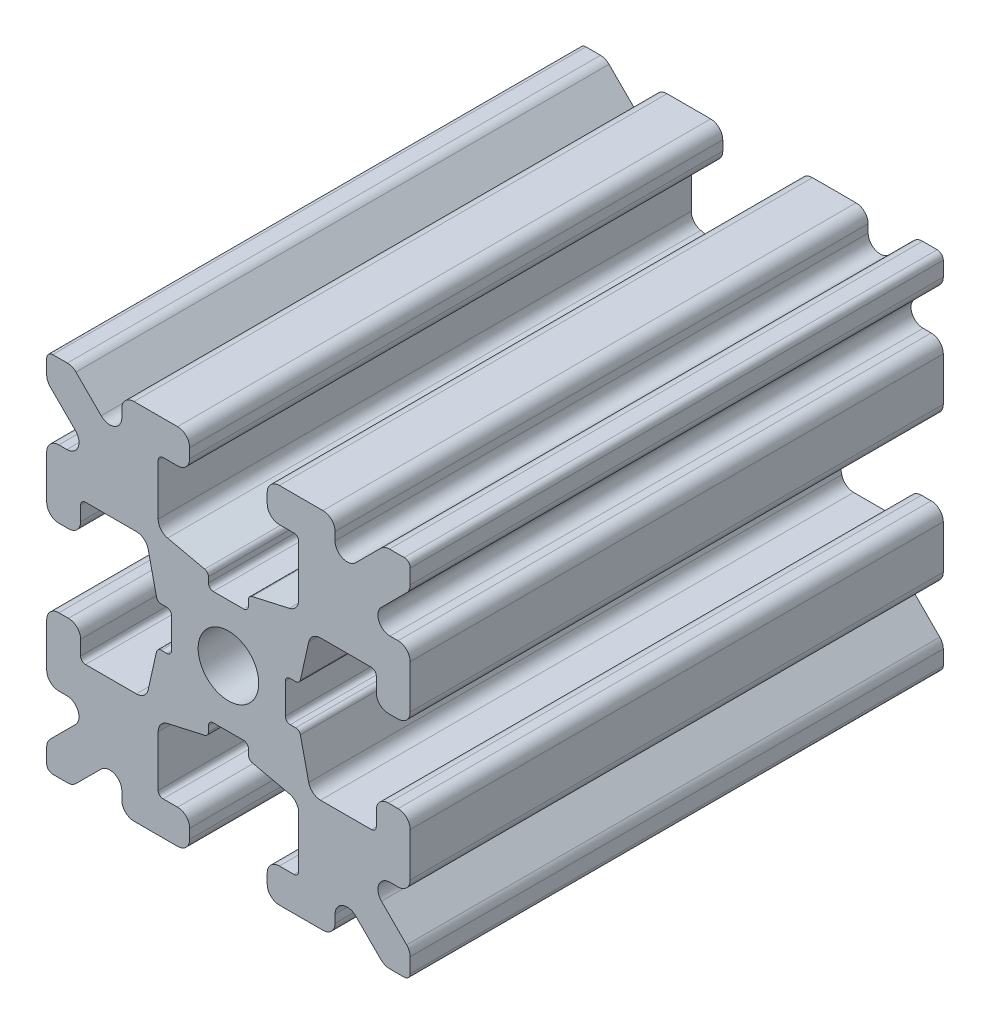
SolidWorks part; units mm, degrees
ref_plane "Front Plane" through (0, 0, 0) normal (0, 0, 1) x (1, 0, 0)
ref_plane "Top Plane" through (0, 0, 0) normal (0, 1, 0) x (1, 0, 0)
ref_plane "Right Plane" through (0, 0, 0) normal (1, 0, 0) x (0, 0, -1)
sketch "Sketch1" plane through (0, 0, 0) normal (0, 0, 1) x (1, 0, 0)
  line L1 (-7.5, -7.5) -> (7.5, -7.5)
  line L2 (-7.5, -7.5) -> (-7.5, 7.5)
  line L3 (-7.5, 7.5) -> (7.5, 7.5)
  line L4 (7.5, -7.5) -> (7.5, 7.5)
  line L5 (-7.5, -7.5) -> (7.5, 7.5) construction
  line L6 (-7.5, 7.5) -> (7.5, -7.5) construction
  circle A0 centre (0, 0) radius 1.25
  point P0 (0, 0)
  dimension "D2" = 2.5
  dimension "D1" = 15
extrude "Boss-Extrude1" add sketch "Sketch1" along normal mid plane 22
fillet "Fillet1" radius 0.25 4 edges at (7.5, -7.5, 0) (-7.5, -7.5, 0) (7.5, 7.5, 0) (-7.5, 7.5, 0)
sketch "Sketch2" plane through (0, 0, 11) normal (0, 0, 1) x (1, 0, 0)
  line L0 (-7.5, 7.25) -> (-7.5, -7.25) construction
  line L1 (-7.5, 1.6) -> (-6.1, 1.6)
  line L2 (-7.5, 1.6) -> (-7.5, -1.6)
  line L3 (-7.5, -1.6) -> (-6.1, -1.6)
  line L4 (-6.1, 1.6) -> (-6.1, 2.9)
  line L5 (0, 0) -> (-12.1036, 0) construction
  line L6 (-6.1, -2.9) -> (-3.4, -2.9)
  line L7 (0, 0) -> (-7.25, 7.25) construction
  line L8 (-6.1, 2.9) -> (-3.4, 2.9)
  line L9 (-3.4, -2.9) -> (-3.4, 2.9)
  line L10 (55, 0) -> (-55, 0) construction
  line L11 (-6.1, -2.9) -> (-6.1, -1.6)
  line L12 (2.9, 6.1) -> (1.6, 6.1)
  line L13 (2.9, 3.4) -> (-2.9, 3.4)
  line L14 (-2.9, 6.1) -> (-2.9, 3.4)
  line L15 (2.9, 6.1) -> (2.9, 3.4)
  line L16 (-1.6, 6.1) -> (-2.9, 6.1)
  line L17 (1.6, 7.5) -> (1.6, 6.1)
  line L18 (-1.6, 7.5) -> (1.6, 7.5)
  line L19 (-1.6, 7.5) -> (-1.6, 6.1)
  line L20 (-1.6, -7.5) -> (-1.6, -6.1)
  line L21 (-1.6, -7.5) -> (1.6, -7.5)
  line L22 (1.6, -7.5) -> (1.6, -6.1)
  line L23 (-1.6, -6.1) -> (-2.9, -6.1)
  line L24 (2.9, -6.1) -> (2.9, -3.4)
  line L25 (-2.9, -6.1) -> (-2.9, -3.4)
  line L26 (2.9, -3.4) -> (-2.9, -3.4)
  line L27 (2.9, -6.1) -> (1.6, -6.1)
  line L28 (6.1, -2.9) -> (6.1, -1.6)
  line L29 (3.4, -2.9) -> (3.4, 2.9)
  line L30 (6.1, 2.9) -> (3.4, 2.9)
  line L31 (6.1, -2.9) -> (3.4, -2.9)
  line L32 (6.1, 1.6) -> (6.1, 2.9)
  line L33 (7.5, -1.6) -> (6.1, -1.6)
  line L34 (7.5, 1.6) -> (7.5, -1.6)
  line L35 (7.5, 1.6) -> (6.1, 1.6)
  dimension "D1" = 3.2
  dimension "D2" = 5.8
  dimension "D3" = 1.4
  dimension "D4" = 2.7
extrude "Cut-Extrude1" cut sketch "Sketch2" against normal through all
sketch "Sketch4" plane through (0, 0, 11) normal (0, 0, 1) x (1, 0, 0)
  line L0 (-3.4, 2.9) -> (-2.75, 0)
  line L1 (55, 0) -> (-55, 0) construction
  line L2 (-2.75, 0) -> (-3.4, -2.9)
  line L3 (-3.4, -2.9) -> (-3.4, 2.9) construction
  line L4 (-3.4, 2.9) -> (-3.4, -2.9)
  line L5 (-2.9, 3.4) -> (0, 2.75)
  line L6 (0, 2.75) -> (2.9, 3.4)
  line L7 (2.9, 3.4) -> (-2.9, 3.4)
  line L8 (3.4, 2.9) -> (2.75, 0)
  line L9 (2.75, 0) -> (3.4, -2.9)
  line L10 (3.4, -2.9) -> (3.4, 2.9)
  line L11 (-2.9, -3.4) -> (0, -2.75)
  line L12 (0, -2.75) -> (2.9, -3.4)
  line L13 (2.9, -3.4) -> (-2.9, -3.4)
  circle A2 centre (0, 0) radius 2.75
  circle A3 centre (0, 0) radius 2.75 construction
  dimension "D1" = 1.5
extrude "Cut-Extrude3" cut sketch "Sketch4" against normal through all
fillet "Fillet3" radius 0.5 16 edges at (-6.1, -1.6, 0) (-7.5, -1.6, 0) (-6.1, 1.6, 0) (-7.5, 1.6, 0) (-1.6, -7.5, 0) (-1.6, -6.1, 0) (1.6, -7.5, 0) (1.6, -6.1, 0) (6.1, -1.6, 0) (7.5, -1.6, 0) (7.5, 1.6, 0) (6.1, 1.6, 0) (1.6, 7.5, 0) (1.6, 6.1, 0) (-1.6, 7.5, 0) (-1.6, 6.1, 0)
fillet "Fillet4" radius 0.5 8 edges at (-3.4, 2.9, 0) (-3.4, -2.9, 0) (2.9, -3.4, 0) (-2.9, -3.4, 0) (3.4, -2.9, 0) (3.4, 2.9, 0) (-2.9, 3.4, 0) (2.9, 3.4, 0)
fillet "Fillet5" radius 3 4 edges at (0, -2.75, 0) (2.75, 0, 0) (-2.75, 0, 0) (0, 2.75, 0)
fillet "Fillet6" radius 0.2 8 edges at (-2.9, -6.1, 0) (2.9, -6.1, 0) (6.1, -2.9, 0) (6.1, 2.9, 0) (2.9, 6.1, 0) (-2.9, 6.1, 0) (-6.1, -2.9, 0) (-6.1, 2.9, 0)
sketch "Sketch5" plane through (0, 0, 11) normal (0, 0, 1) x (1, 0, 0)
  line L0 (0, 0) -> (-7.25, 7.25) construction
  line L1 (-7.5, 6.4393) -> (-5.4607, 4.4)
  line L2 (-6.4393, 7.5) -> (-4.4, 5.4607)
  line L3 (-7.5, 4.4) -> (-5.4607, 4.4)
  line L4 (-3.8003, 2.9) -> (-5.9, 2.9) construction
  line L5 (0, 0) -> (-12.1819, 0) construction
  line L6 (-4.4, 7.5) -> (-4.4, 5.4607)
  line L7 (-2.9, 5.9) -> (-2.9, 3.8003) construction
  line L8 (-7.5, 6.4393) -> (-7.5, 4.4)
  line L9 (-7.5, 7.25) -> (-7.5, 2.1) construction
  line L10 (2.1, -7.5) -> (7.25, -7.5) construction
  line L11 (7.5, -7.25) -> (7.5, -2.1) construction
  line L12 (7.25, 7.5) -> (2.1, 7.5) construction
  line L13 (-2.1, 7.5) -> (-7.25, 7.5) construction
  line L14 (-4.4, 7.5) -> (-6.4393, 7.5)
  line L16 (55, 0) -> (-55, 0) construction
  line L17 (0, 0) -> (0, 10.993) construction
  line L18 (0, -54.6431) -> (0, 54.6431) construction
  line L20 (4.4, 7.5) -> (6.4393, 7.5)
  line L22 (7.5, 6.4393) -> (7.5, 4.4)
  line L23 (4.4, 7.5) -> (4.4, 5.4607)
  line L24 (7.5, 4.4) -> (5.4607, 4.4)
  line L25 (6.4393, 7.5) -> (4.4, 5.4607)
  line L26 (7.5, 6.4393) -> (5.4607, 4.4)
  line L27 (7.5, -6.4393) -> (5.4607, -4.4)
  line L28 (6.4393, -7.5) -> (4.4, -5.4607)
  line L29 (7.5, -4.4) -> (5.4607, -4.4)
  line L30 (4.4, -7.5) -> (4.4, -5.4607)
  line L31 (7.5, -6.4393) -> (7.5, -4.4)
  line L33 (4.4, -7.5) -> (6.4393, -7.5)
  line L36 (-4.4, -7.5) -> (-6.4393, -7.5)
  line L38 (-7.5, -6.4393) -> (-7.5, -4.4)
  line L39 (-4.4, -7.5) -> (-4.4, -5.4607)
  line L40 (-7.5, -4.4) -> (-5.4607, -4.4)
  line L41 (-6.4393, -7.5) -> (-4.4, -5.4607)
  line L42 (-7.5, -6.4393) -> (-5.4607, -4.4)
  dimension "D1" = 1.5
  dimension "D2" = 1.5
  dimension "D3" = 1.5
extrude "Cut-Extrude4" cut sketch "Sketch5" against normal through all
fillet "Fillet8" radius 0.5 24 edges at (-5.4607, 4.4, 0) (-7.5, 4.4, 0) (-5.4607, -4.4, 0) (-7.5, -4.4, 0) (-4.4, -7.5, 0) (-4.4, -5.4607, 0) (4.4, -7.5, 0) (4.4, -5.4607, 0) (5.4607, -4.4, 0) (7.5, -4.4, 0) (7.5, 4.4, 0) (5.4607, 4.4, 0) (4.4, 5.4607, 0) (4.4, 7.5, 0) (-4.4, 5.4607, 0) (-4.4, 7.5, 0) (-6.4393, 7.5, 0) (-7.5, 6.4393, 0) (6.4393, 7.5, 0) (7.5, 6.4393, 0) (6.4393, -7.5, 0) (7.5, -6.4393, 0) (-6.4393, -7.5, 0) (-7.5, -6.4393, 0)
sketch "Sketch6" plane through (0, 0, 11) normal (0, 0, 1) x (1, 0, 0)
  line L0 (0, 0) -> (0, 11.013) construction
  line L1 (0.6561, 2.8971) -> (2.1235, 2.8971) construction
  line L2 (0, -54.6431) -> (0, 54.6431) construction
  line L3 (0, 0) -> (7.25, 7.25) construction
  line L4 (7.5, 0.8255) -> (7.5, -0.8255)
  line L5 (2.3471, 0.8255) -> (7.5, 0.8255)
  line L6 (0, 0) -> (12.4016, 0) construction
  line L7 (0.8255, -7.5) -> (-0.8255, -7.5)
  line L8 (2.3471, -0.8255) -> (2.3471, 0.8255)
  line L9 (0.8255, -2.3471) -> (0.8255, -7.5)
  line L10 (7.5, -0.8255) -> (2.3471, -0.8255)
  line L11 (-7.5, -0.8255) -> (-2.3471, -0.8255)
  line L12 (-2.3471, -0.8255) -> (-2.3471, 0.8255)
  line L13 (-0.8255, -2.3471) -> (0.8255, -2.3471)
  line L14 (-0.8255, 7.5) -> (-0.8255, 2.3471)
  line L15 (-0.8255, 2.3471) -> (0.8255, 2.3471)
  line L16 (-0.8255, -7.5) -> (-0.8255, -2.3471)
  line L17 (0.8255, 2.3471) -> (0.8255, 7.5)
  line L18 (0.8255, 7.5) -> (-0.8255, 7.5)
  line L19 (3.9, 7.5) -> (2.1, 7.5) construction
  line L20 (-2.3471, 0.8255) -> (-7.5, 0.8255)
  line L21 (-7.5, 0.8255) -> (-7.5, -0.8255)
  point P5 (0, -2.5973)
  point P7 (0, 2.5973)
  dimension "D3" = 0.55
  dimension "D1" = 1.651
extrude "Cut-Extrude5" cut sketch "Sketch6" against normal through all
fillet "Fillet10" radius 0.2 16 edges at (-2.935, 0.8255, 0) (-2.935, -0.8255, 0) (2.935, -0.8255, 0) (2.935, 0.8255, 0) (0.8255, 2.935, 0) (-0.8255, 2.935, 0) (-2.3471, 0.8255, 0) (-2.3471, -0.8255, 0) (0.8255, 2.3471, 0) (-0.8255, 2.3471, 0) (2.3471, 0.8255, 0) (2.3471, -0.8255, 0) (0.8255, -2.935, 0) (0.8255, -2.3471, 0) (-0.8255, -2.3471, 0) (-0.8255, -2.935, 0)
